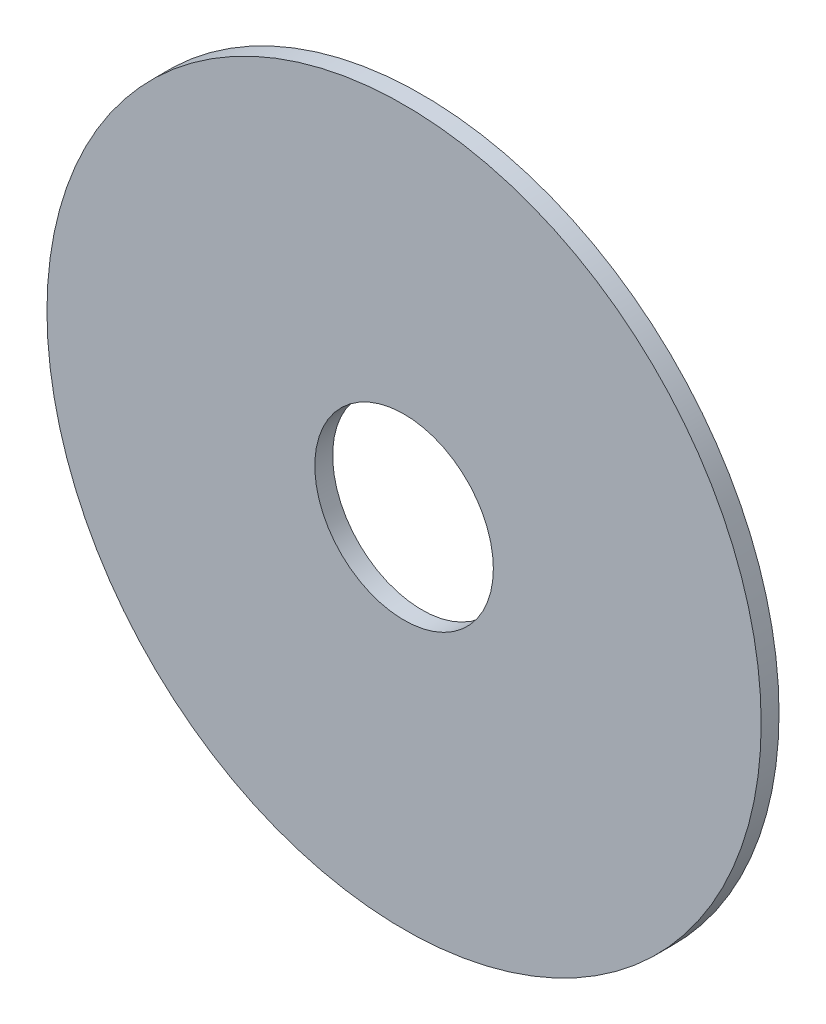
SolidWorks part; units mm, degrees
ref_plane "Front Plane" through (0, 0, 0) normal (0, 0, 1) x (1, 0, 0)
ref_plane "Top Plane" through (0, 0, 0) normal (0, 1, 0) x (1, 0, 0)
ref_plane "Right Plane" through (0, 0, 0) normal (1, 0, 0) x (0, 0, -1)
sketch "Sketch1" plane through (0, 0, 0) normal (0, 0, 1) x (1, 0, 0)
  line L0 (0, 0) -> (0, 50) construction
  circle A0 centre (0, 0) radius 50
  circle A1 centre (0, 0) radius 12.5
  point P16 (0, 0)
  dimension "D2" = 25
  dimension "D3" = 100
extrude "Boss-Extrude1" add sketch "Sketch1" along normal blind 2.5
